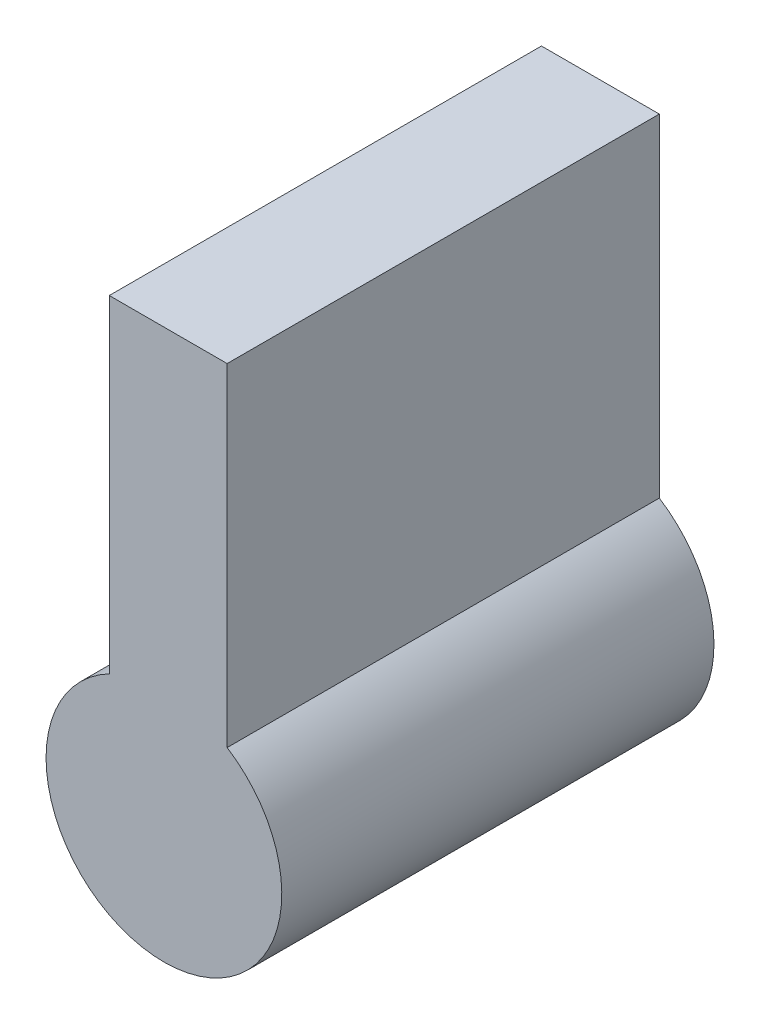
SolidWorks part; units mm, degrees
ref_plane "Alzado" through (0, 0, 0) normal (0, 0, 1) x (1, 0, 0)
ref_plane "Planta" through (0, 0, 0) normal (0, 1, 0) x (1, 0, 0)
ref_plane "Vista lateral" through (0, 0, 0) normal (1, 0, 0) x (0, 0, -1)
sketch "Croquis1" plane through (0, 0, 0) normal (0, 0, 1) x (1, 0, 0)
  circle A2 centre (0, 0) radius 6
  circle A3 centre (0, 0) radius 4
  circle A4 centre (0, 0) radius 4 construction
  dimension "D1" = 2
extrude "Saliente-Extruir1" add sketch "Croquis1" along normal blind 20
sketch "Croquis2" plane through (0, 0, 20) normal (0, 0, 1) x (1, 0, 0)
  circle A2 centre (0, 0) radius 6
  circle A3 centre (0, 0) radius 6 construction
extrude "Saliente-Extruir2" add sketch "Croquis2" along normal blind 2
sketch "Croquis3" plane through (0, 0, 0) normal (0, 0, -1) x (-1, 0, 0)
  line L0 (-0.2184, 3.994) -> (-0.2184, 21.994) construction
  line L1 (-0.2184, 21.994) -> (-3.2184, 21.994)
  line L2 (-3.2184, 21.994) -> (-3.2184, 3.994)
  line L3 (-3.2184, 3.994) -> (2.7816, 3.994)
  line L4 (2.7816, 3.994) -> (2.7816, 21.994)
  line L5 (2.7816, 21.994) -> (-0.2184, 21.994)
  circle A0 centre (0, 0) radius 4 construction
  dimension "D1" = 18
  dimension "D2" = 6
  dimension "D3" = 3
extrude "Saliente-Extruir3" add sketch "Croquis3" against normal up to surface (22 mm away) up to face at (6, 0, 22)
